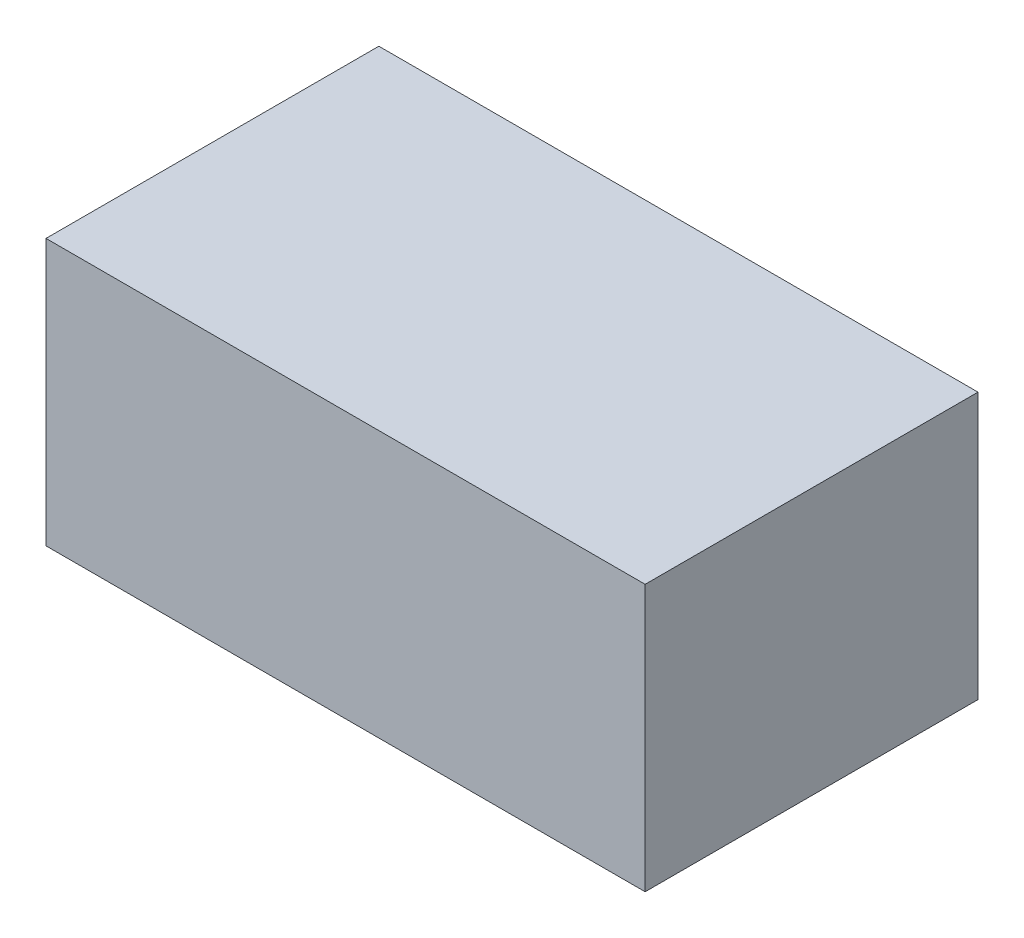
SolidWorks part; units mm, degrees
ref_plane "Front Plane" through (0, 0, 0) normal (0, 0, 1) x (1, 0, 0)
ref_plane "Top Plane" through (0, 0, 0) normal (0, 1, 0) x (1, 0, 0)
ref_plane "Right Plane" through (0, 0, 0) normal (1, 0, 0) x (0, 0, -1)
sketch "Sketch1" plane through (0, 0, 0) normal (0, 0, 1) x (1, 0, 0)
  line L1 (-36, 16) -> (36, 16)
  line L2 (-36, 16) -> (-36, -16)
  line L3 (-36, -16) -> (36, -16)
  line L4 (36, 16) -> (36, -16)
  line L5 (-36, 16) -> (36, -16) construction
  line L6 (-36, -16) -> (36, 16) construction
  point P0 (0, 0)
  dimension "D1" = 72
  dimension "D2" = 32
extrude "Boss-Extrude1" add sketch "Sketch1" against normal blind 40
